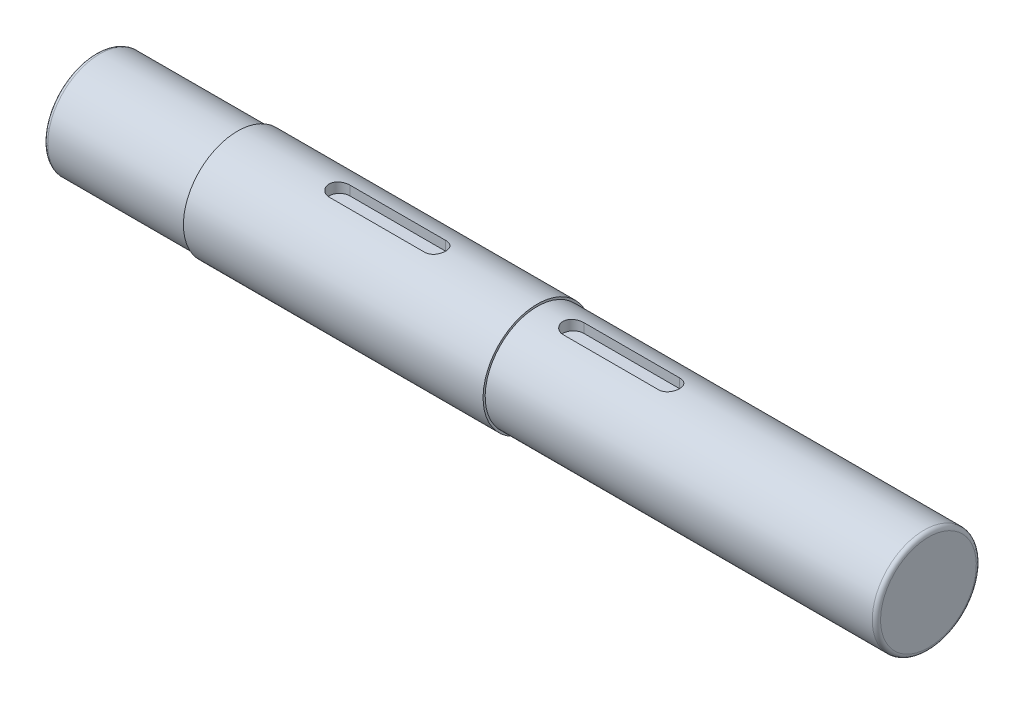
SolidWorks part; units mm, degrees
ref_plane "Front Plane" through (0, 0, 0) normal (0, 0, 1) x (1, 0, 0)
ref_plane "Top Plane" through (0, 0, 0) normal (0, 1, 0) x (1, 0, 0)
ref_plane "Right Plane" through (0, 0, 0) normal (1, 0, 0) x (0, 0, -1)
sketch "Sketch1" plane through (0, 0, 0) normal (0, 0, 1) x (1, 0, 0)
  line L0 (-88.4097, 0) -> (111.6903, 0) construction
  line L1 (111.6903, 0) -> (111.6903, 12.5)
  line L2 (111.6903, 12.5) -> (17.6903, 12.5)
  line L3 (17.6903, 12.5) -> (17.6903, 13)
  line L4 (17.6903, 13) -> (-54.3097, 13)
  line L5 (-54.3097, 13) -> (-54.3097, 12.5)
  line L6 (-54.3097, 12.5) -> (-88.4097, 12.5)
  line L7 (-88.4097, 12.5) -> (-88.4097, 0)
  line L8 (-88.4097, 0) -> (111.6903, 0)
  dimension "D1" = 94
  dimension "D2" = 72
  dimension "D3" = 12.5
  dimension "D4" = 0.5
  dimension "D5" = 34.1
  dimension "D6" = 12.5
revolve "Revolve1" add sketch "Sketch1" angle 360 about L0
ref_plane "Plane2" through (0, 12.5, 0) normal (0, 1, 0) x (1, 0, 0)
sketch "Sketch2" plane through (0, 12.5, 0) normal (0, 1, 0) x (1, 0, 0)
  line L0 (17.6903, 0) -> (111.6903, 0) construction
  line L1 (17.6903, -12.5) -> (17.6903, 12.5) construction
  line L2 (111.6903, -12.5) -> (111.6903, 12.5) construction
  line L3 (26.3903, 0) -> (49.3903, 0) construction
  line L4 (26.3903, 2.5) -> (49.3903, 2.5)
  line L5 (26.3903, -2.5) -> (49.3903, -2.5)
  arc A0 (26.3903, 2.5) -> (26.3903, -2.5) centre (26.3903, 0) ccw
  arc A1 (49.3903, -2.5) -> (49.3903, 2.5) centre (49.3903, 0) ccw
  point P8 (37.8903, 0)
  point P13 (23.8903, 0)
  point P14 (51.8903, 0)
  dimension "D1" = 28
  dimension "D2" = 5
  dimension "D3" = 6.2
  dimension "D4" = 23
other "AlignGroup1"
extrude "Cut-Extrude1" cut sketch "Sketch2" against normal blind 2.5
fillet "Fillet4" radius 1 1 edges at (111.6903, -12.5, 0)
fillet "Fillet5" radius 1 1 edges at (-88.4097, -12.5, 0)
ref_plane "Plane3" through (0, 13, 0) normal (0, 1, 0) x (1, 0, 0)
sketch "Sketch3" plane through (0, 13, 0) normal (0, 1, 0) x (1, 0, 0)
  line L0 (-29.8097, 0) -> (-6.8097, 0) construction
  line L1 (17.6903, 0) -> (-54.3097, 0) construction
  line L2 (-29.8097, 2.5) -> (-6.8097, 2.5)
  line L3 (-29.8097, -2.5) -> (-6.8097, -2.5)
  line L5 (-54.3097, 13) -> (-54.3097, -13) construction
  arc A0 (-29.8097, 2.5) -> (-29.8097, -2.5) centre (-29.8097, 0) ccw
  arc A1 (-6.8097, -2.5) -> (-6.8097, 2.5) centre (-6.8097, 0) ccw
  point P5 (-18.3097, 0)
  point P12 (-32.3097, 0)
  dimension "D1" = 23
  dimension "D3" = 5
  dimension "D2" = 24.5
  dimension "D4" = 22
extrude "Cut-Extrude3" cut sketch "Sketch3" against normal blind 2.5
